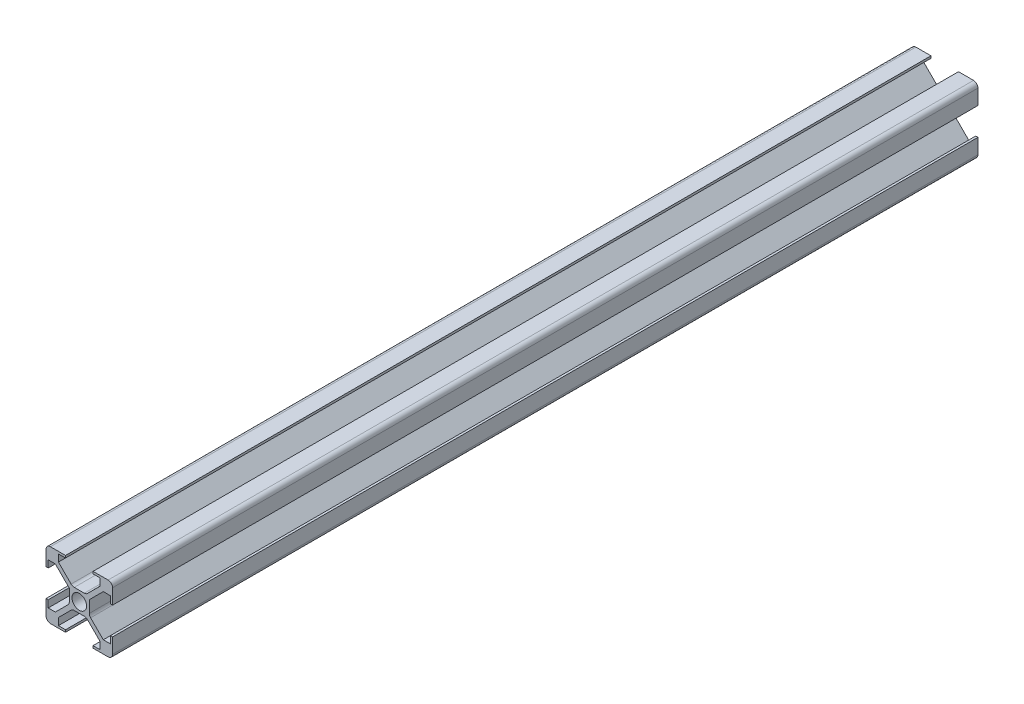
SolidWorks part; units mm, degrees
ref_plane "前视基准面" through (0, 0, 0) normal (0, 0, 1) x (1, 0, 0)
ref_plane "上视基准面" through (0, 0, 0) normal (0, 1, 0) x (1, 0, 0)
ref_plane "右视基准面" through (0, 0, 0) normal (1, 0, 0) x (0, 0, -1)
sketch "草图1" plane through (0, 0, 0) normal (0, 0, 1) x (1, 0, 0)
  line L0 (0, 0) -> (7.5, 0) construction
  line L1 (0, 0) -> (0, 7.5) construction
  line L2 (7.5, 7.5) -> (0, 0) construction
  line L3 (7.5, 7.5) -> (7.5, 3.1)
  line L4 (7.5, 3.1) -> (7, 3.1)
  line L5 (7, 3.1) -> (7, 4.7)
  line L6 (7, 4.7) -> (5.4071, 4.7)
  line L7 (5.4071, 4.7) -> (2.2549, 1.5478)
  line L8 (2.2549, 1.5478) -> (2.2549, 0)
  line L9 (1.5478, 2.2549) -> (0, 2.2549)
  line L10 (4.7, 5.4071) -> (1.5478, 2.2549)
  line L11 (4.7, 7) -> (4.7, 5.4071)
  line L12 (3.1, 7) -> (4.7, 7)
  line L13 (3.1, 7.5) -> (3.1, 7)
  line L14 (7.5, 7.5) -> (3.1, 7.5)
  line L15 (7.5, -7.5) -> (3.1, -7.5)
  line L16 (3.1, -7.5) -> (3.1, -7)
  line L17 (3.1, -7) -> (4.7, -7)
  line L18 (4.7, -7) -> (4.7, -5.4071)
  line L19 (4.7, -5.4071) -> (1.5478, -2.2549)
  line L20 (1.5478, -2.2549) -> (0, -2.2549)
  line L21 (2.2549, -1.5478) -> (2.2549, 0)
  line L22 (5.4071, -4.7) -> (2.2549, -1.5478)
  line L23 (7, -4.7) -> (5.4071, -4.7)
  line L24 (7, -3.1) -> (7, -4.7)
  line L25 (7.5, -3.1) -> (7, -3.1)
  line L26 (7.5, -7.5) -> (7.5, -3.1)
  line L27 (0, 0) -> (7.5, 0) construction
  line L28 (7.5, -7.5) -> (0, 0) construction
  line L29 (-7.5, -7.5) -> (-7.5, -3.1)
  line L30 (-7.5, -3.1) -> (-7, -3.1)
  line L31 (-7, -3.1) -> (-7, -4.7)
  line L32 (-7, -4.7) -> (-5.4071, -4.7)
  line L33 (-5.4071, -4.7) -> (-2.2549, -1.5478)
  line L34 (-2.2549, -1.5478) -> (-2.2549, 0)
  line L35 (-1.5478, -2.2549) -> (0, -2.2549)
  line L36 (-4.7, -5.4071) -> (-1.5478, -2.2549)
  line L37 (-4.7, -7) -> (-4.7, -5.4071)
  line L38 (-3.1, -7) -> (-4.7, -7)
  line L39 (-3.1, -7.5) -> (-3.1, -7)
  line L40 (-7.5, -7.5) -> (-3.1, -7.5)
  line L41 (0, 0) -> (0, -7.5) construction
  line L42 (-7.5, -7.5) -> (0, 0) construction
  line L43 (-7.5, 7.5) -> (-3.1, 7.5)
  line L44 (-3.1, 7.5) -> (-3.1, 7)
  line L45 (-3.1, 7) -> (-4.7, 7)
  line L46 (-4.7, 7) -> (-4.7, 5.4071)
  line L47 (-4.7, 5.4071) -> (-1.5478, 2.2549)
  line L48 (-1.5478, 2.2549) -> (0, 2.2549)
  line L49 (-2.2549, 1.5478) -> (-2.2549, 0)
  line L50 (-5.4071, 4.7) -> (-2.2549, 1.5478)
  line L51 (-7, 4.7) -> (-5.4071, 4.7)
  line L52 (-7, 3.1) -> (-7, 4.7)
  line L53 (-7.5, 3.1) -> (-7, 3.1)
  line L54 (-7.5, 7.5) -> (-7.5, 3.1)
  line L55 (0, 0) -> (-7.5, 0) construction
  line L56 (-7.5, 7.5) -> (0, 0) construction
  circle A0 centre (0, 0) radius 1.65
  point P63 (0, 0)
  dimension "D7" = 3.3
  dimension "D1" = 7.5
  dimension "D2" = 7.5
  dimension "D3" = 4.4
  dimension "D4" = 1.6
  dimension "D5" = 0.5
  dimension "D6" = 0.5
  dimension "D8" = 4
extrude "凸台-拉伸1" add sketch "草图1" along normal blind 195
fillet "圆角1" radius 1 10 edges at (-1.5478, -2.2549, 97.5) (1.5478, -2.2549, 97.5) (-2.2549, -1.5478, 97.5) (-1.5478, 2.2549, 97.5) (1.5478, 2.2549, 97.5) (2.2549, -1.5478, 97.5) (-7.5, -7.5, 97.5) (7.5, -7.5, 97.5) (-7.5, 7.5, 97.5) (7.5, 7.5, 97.5)
